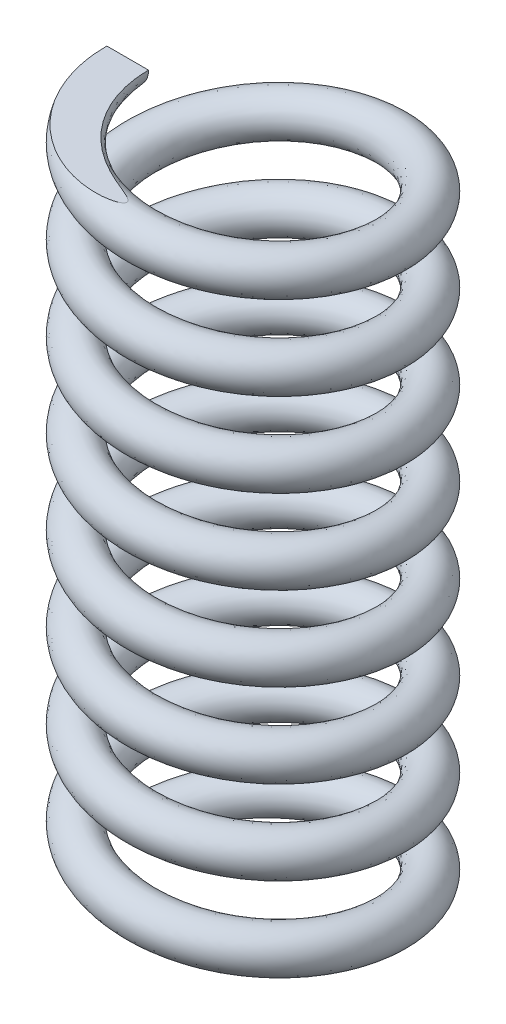
SolidWorks part; units mm, degrees
ref_plane "Front Plane" through (0, 0, 0) normal (0, 0, 1) x (1, 0, 0)
ref_plane "Top Plane" through (0, 0, 0) normal (0, 1, 0) x (1, 0, 0)
ref_plane "Right Plane" through (0, 0, 0) normal (1, 0, 0) x (0, 0, -1)
sketch "Sketch1" plane through (0, 0, 0) normal (0, 1, 0) x (1, 0, 0)
  circle A0 centre (0, 0) radius 9.9
  dimension "D1" = 19.8
curve "Helix/Spiral1" pitch 6.63 height 53.04 turns 8
sketch "Sketch4" plane through (0, 0, 0) normal (0, 0, 1) x (1, 0, 0)
  circle A0 centre (-9.9, 0) radius 1.65
  point P2 (0, 0)
  dimension "D1" = 3.3
  dimension "D2" = 9.9
sweep "Sweep1" add profiles "Sketch4" path "Helix/Spiral1"
sketch "Sketch6" plane through (0, 0, 0) normal (0, 1, 0) x (1, 0, 0)
  circle A0 centre (0, 0) radius 20
  dimension "D1" = 40
extrude "Cut-Extrude1" cut sketch "Sketch6" against normal blind 10
ref_plane "Plane2" through (0, 53.04, 0) normal (0, 1, 0) x (1, 0, 0)
sketch "Sketch9" plane through (0, 53.04, 0) normal (0, 1, 0) x (1, 0, 0)
  circle A0 centre (0, 0) radius 15
  dimension "D1" = 30
extrude "Cut-Extrude2" cut sketch "Sketch9" along normal blind 10
